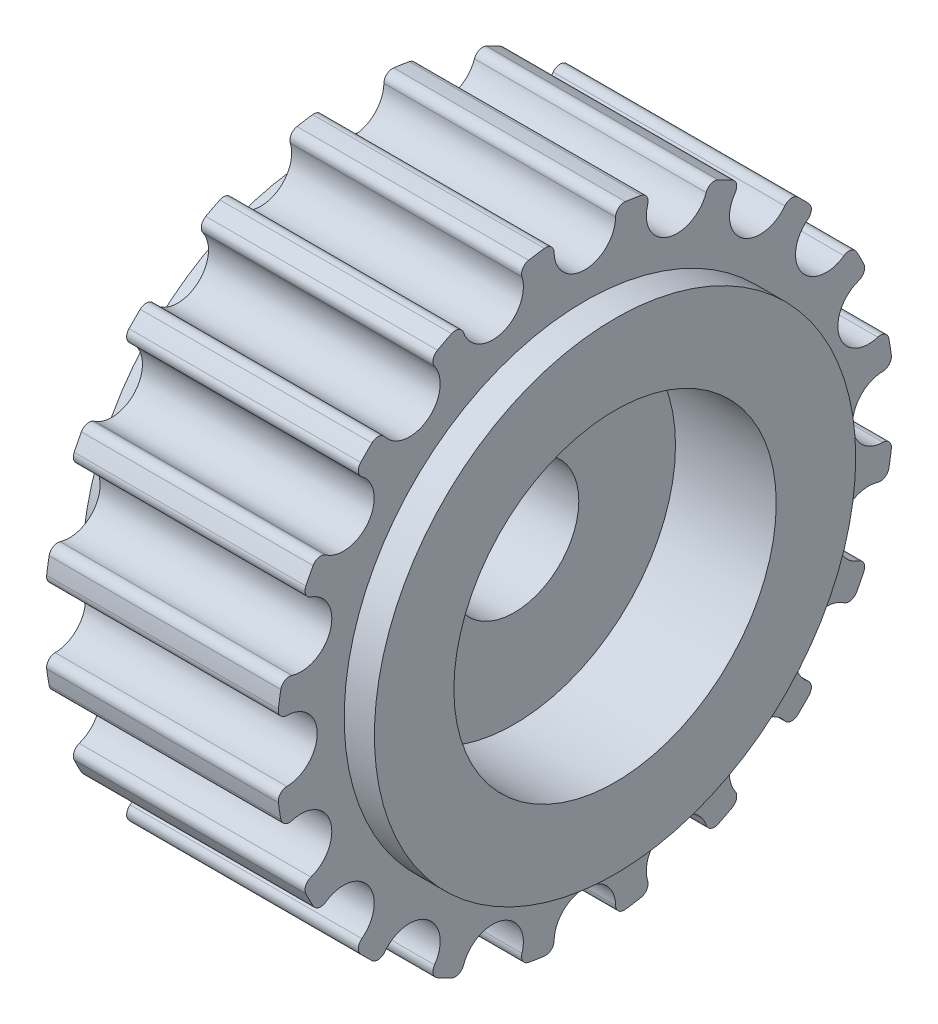
SolidWorks part; units mm, degrees
ref_plane "Front" through (0, 0, 0) normal (0, 0, 1) x (1, 0, 0)
ref_plane "Top" through (0, 0, 0) normal (0, 1, 0) x (1, 0, 0)
ref_plane "Right" through (0, 0, 0) normal (1, 0, 0) x (0, 0, -1)
sketch "Sketch1" plane through (0, 0, 0) normal (1, 0, 0) x (0, 0, -1)
  line L0 (0, 14.81) -> (0, 0) construction
  line L1 (0, 0) -> (4.5765, 14.0851) construction
  line L2 (0, 13.285) -> (0, 0)
  line L3 (0, 0) -> (4.1053, 12.6348)
  circle A0 centre (0, 0) radius 13.285 construction
  circle A1 centre (0, 0) radius 15.345 construction
  circle A2 centre (0, 14.81) radius 1.525 construction
  circle A3 centre (1.9549, 14.7863) radius 0.43 construction
  circle A4 centre (4.5765, 14.0851) radius 1.525 construction
  circle A5 centre (2.7101, 14.6667) radius 0.43 construction
  arc A6 (0, 13.285) -> (1.5249, 14.7915) centre (0, 14.81) ccw
  arc A7 (2.0112, 15.2126) -> (1.5249, 14.7915) centre (1.9549, 14.7863) ccw
  arc A8 (2.7882, 15.0896) -> (2.0112, 15.2126) centre (0, 0) ccw
  arc A9 (3.1206, 14.5388) -> (2.7882, 15.0896) centre (2.7101, 14.6667) ccw
  arc A10 (3.1206, 14.5388) -> (4.1053, 12.6348) centre (4.5765, 14.0851) ccw
  dimension "D1" = 2.06
  dimension "D2" = 30.69
  dimension "D3" = 3.05
  dimension "D4" = 0.86
  dimension "D5" = 18
extrude "Boss-Extrude1" add sketch "Sketch1" along normal mid plane 11.5
pattern_circular "CirPattern1" count 20 over 360 about axis through (0, 0, 0) along (1, 0, 0) of "Boss-Extrude1"
sketch "Sketch2" plane through (5.75, 0, 0) normal (1, 0, 0) x (0, 0, -1)
  circle A0 centre (0, 0) radius 11.945
  arc A1 (2.7882, 15.0896) -> (2.0112, 15.2126) centre (0, 0) ccw construction
  dimension "D1" = 3.4
extrude "Boss-Extrude2" add sketch "Sketch2" along normal blind 1.5
sketch "Sketch4" plane through (7.25, 0, 0) normal (1, 0, 0) x (0, 0, -1)
  circle A0 centre (0, 0) radius 8
  dimension "D1" = 16
extrude "Cut-Extrude2" cut sketch "Sketch4" against normal blind 5
mirror "Mirror1" about plane through (0, 0, 0) normal (1, 0, 0) of "Cut-Extrude2", "Boss-Extrude2"
sketch "Sketch3" plane through (7.25, 0, 0) normal (1, 0, 0) x (0, 0, -1)
  circle A0 centre (0, 0) radius 3.2
  dimension "D1" = 6.4
extrude "Cut-Extrude1" cut sketch "Sketch3" against normal up to surface (14.5 mm away) up to face at (-7.25, 0, -8)
equation "\"D2\"=26.57"
